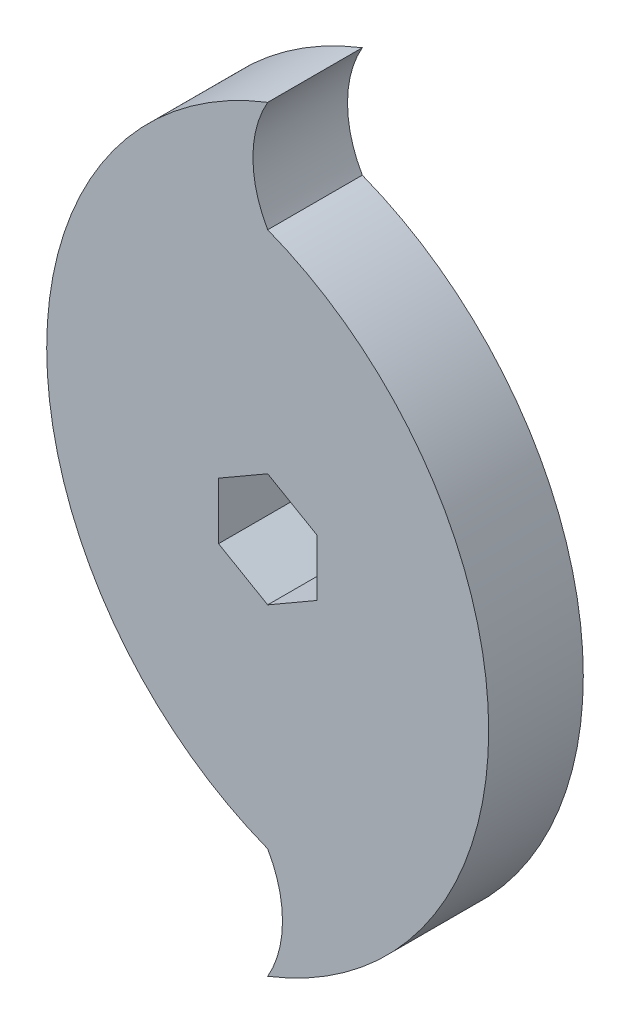
SolidWorks part; units mm, degrees
material "1.5805 (10NiCr5-4)"
ref_plane "Plan de face" through (0, 0, 0) normal (0, 0, 1) x (1, 0, 0)
ref_plane "Plan de dessus" through (0, 0, 0) normal (0, 1, 0) x (1, 0, 0)
ref_plane "Plan de droite" through (0, 0, 0) normal (1, 0, 0) x (0, 0, -1)
sketch "Esquisse1" plane through (0, 0, 0) normal (0, 0, 1) x (1, 0, 0)
  line L0 (0, 0) -> (0, -240) construction
  arc A0 (0, -205) -> (0, 0) centre (39.9218, -102.5) cw
  arc A1 (0, -35) -> (0, 0) centre (30.3109, -17.5) cw
  arc A2 (0, -205) -> (0, -240) centre (-30.3109, -222.5) cw
  arc A3 (0, -35) -> (0, -240) centre (-39.9218, -137.5) cw
  dimension "D3" = 35
  dimension "D4" = 110
  dimension "D6" = 35
  dimension "D5" = 35
  dimension "D7" = 110
  dimension "D1" = 240
  dimension "D2" = 35
extrude "Boss.-Extru.2" add sketch "Esquisse1" along normal blind 30
sketch "Esquisse2" plane through (0, 0, 30) normal (0, 0, 1) x (1, 0, 0)
  line L0 (0, 0) -> (0, -240) construction
  line L1 (-70.0782, -102.5) -> (70.0782, -137.5) construction
  line L3 (15.5885, -111) -> (0, -102)
  line L4 (0, -102) -> (-15.5885, -111)
  line L5 (-15.5885, -111) -> (-15.5885, -129)
  line L6 (-15.5885, -129) -> (0, -138)
  line L7 (0, -138) -> (15.5885, -129)
  line L8 (15.5885, -129) -> (15.5885, -111)
  arc A0 (0, 0) -> (0, -205) centre (39.9218, -102.5) ccw construction
  arc A1 (0, -240) -> (0, -35) centre (-39.9218, -137.5) ccw construction
  circle A2 centre (0, -120) radius 15.5885 construction
  dimension "D1" = 18
extrude "Enlèv. mat.-Extru.1" cut sketch "Esquisse2" against normal through all
